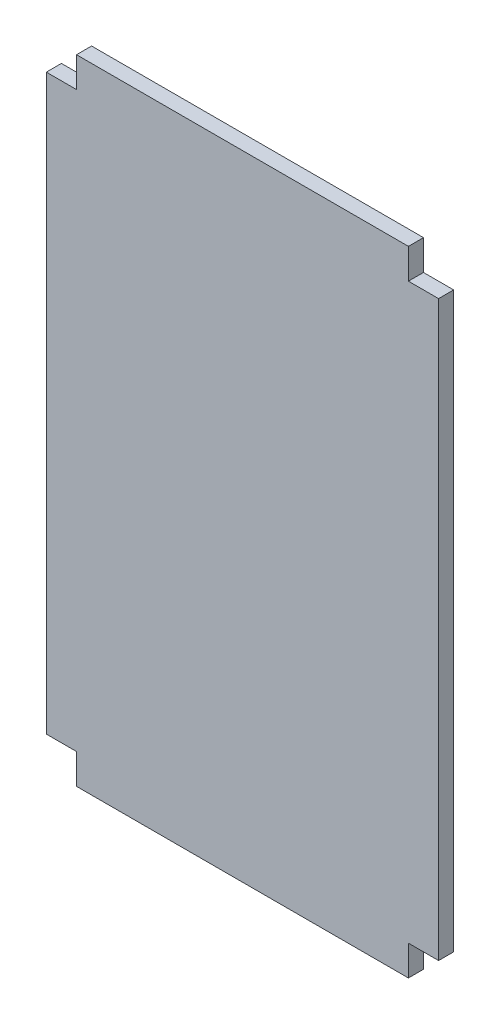
SolidWorks part; units mm, degrees
material "Oak"
ref_plane "Front Plane" through (0, 0, 0) normal (0, 0, 1) x (1, 0, 0)
ref_plane "Top Plane" through (0, 0, 0) normal (0, 1, 0) x (1, 0, 0)
ref_plane "Right Plane" through (0, 0, 0) normal (1, 0, 0) x (0, 0, -1)
sketch "Sketch2" plane through (0, 0, 0) normal (0, 0, 1) x (1, 0, 0)
  line L1 (0, 0) -> (520, 0)
  line L2 (0, 0) -> (0, 840)
  line L3 (0, 840) -> (520, 840)
  line L4 (520, 0) -> (520, 840)
  dimension "D1" = 520
  dimension "D2" = 840
extrude "Boss-Extrude1" add sketch "Sketch2" along normal blind 20
sketch "Sketch3" plane through (0, 0, 0) normal (0, 0, -1) x (-1, 0, 0)
  line L1 (-520, 840) -> (-480, 840)
  line L2 (-520, 840) -> (-520, 800)
  line L3 (-520, 800) -> (-480, 800)
  line L4 (-480, 840) -> (-480, 800)
  line L5 (0, 840) -> (-40, 840)
  line L6 (0, 840) -> (0, 800)
  line L7 (0, 800) -> (-40, 800)
  line L8 (-40, 840) -> (-40, 800)
  line L9 (-520, 0) -> (-480, 0)
  line L10 (-520, 0) -> (-520, 40)
  line L11 (-520, 40) -> (-480, 40)
  line L12 (-480, 0) -> (-480, 40)
  line L13 (0, 0) -> (-40, 0)
  line L14 (0, 0) -> (0, 40)
  line L15 (0, 40) -> (-40, 40)
  line L16 (-40, 0) -> (-40, 40)
  dimension "D1" = 40
  dimension "D2" = 40
  dimension "D3" = 40
  dimension "D4" = 40
  dimension "D5" = 40
  dimension "D6" = 40
extrude "Cut-Extrude1" cut sketch "Sketch3" against normal blind 30
